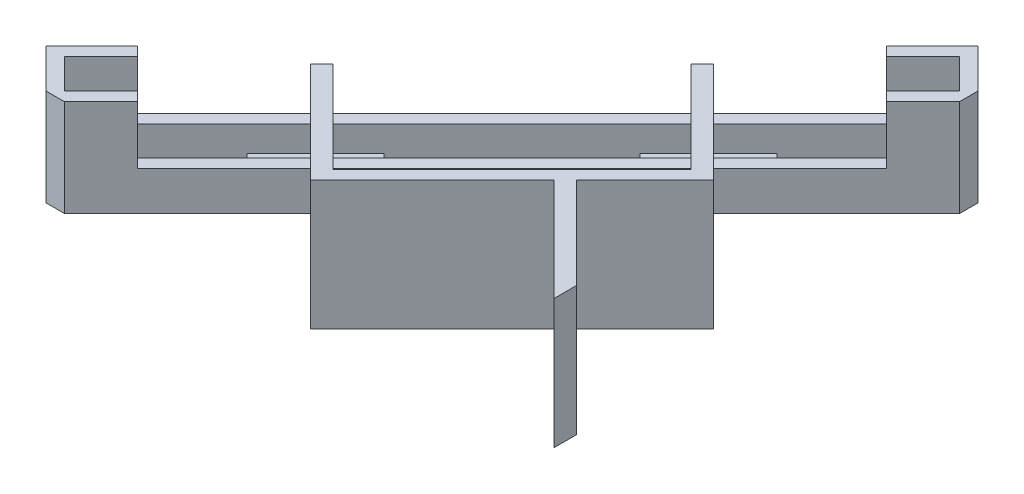
SolidWorks part; units mm, degrees
ref_plane "Front" through (0, 0, 0) normal (0, 0, 1) x (1, 0, 0)
ref_plane "Top" through (0, 0, 0) normal (0, 1, 0) x (1, 0, 0)
ref_plane "Right" through (0, 0, 0) normal (1, 0, 0) x (0, 0, -1)
sketch "Sketch1" plane through (0, 0, 0) normal (0, 1, 0) x (1, 0, 0)
  line L0 (-91.5986, 0) -> (0, 0)
  line L1 (0, 0) -> (0, 91.5986)
  line L2 (0, 91.5986) -> (-91.5986, 0)
  dimension "D1" = 129.54
extrude "Boss-Extrude1" add sketch "Sketch1" along normal blind 25.4
sketch "Sketch2" plane through (-45.7993, 0, -45.7993) normal (-0.7071, 0, -0.7071) x (-0.7071, 0, 0.7071)
  line L0 (-64.77, 19.05) -> (-62.23, 19.05)
  line L1 (-64.77, 25.4) -> (-64.77, 0) construction
  line L2 (-62.23, 19.05) -> (-62.23, 2.54)
  line L3 (-62.23, 2.54) -> (62.23, 2.54)
  line L4 (62.23, 2.54) -> (62.23, 19.05)
  line L5 (62.23, 19.05) -> (64.77, 19.05)
  line L6 (64.77, 25.4) -> (64.77, 0) construction
  line L7 (-64.77, 0) -> (64.77, 0) construction
  line L8 (-64.77, 25.4) -> (64.77, 25.4) construction
  line L9 (-64.77, 19.05) -> (-64.77, 0)
  line L10 (-64.77, 0) -> (64.77, 0)
  line L11 (64.77, 0) -> (64.77, 19.05)
  dimension "D1" = 2.54
  dimension "D2" = 2.54
  dimension "D3" = 2.54
  dimension "D4" = 6.35
  dimension "D5" = 6.35
extrude "Boss-Extrude2" add sketch "Sketch2" along normal blind 8.255
sketch "Sketch3" plane through (-51.6365, 0, -51.6365) normal (-0.7071, 0, -0.7071) x (-0.7071, 0, 0.7071)
  line L1 (-64.77, 0) -> (64.77, 0)
  line L2 (-64.77, 0) -> (-64.77, 19.05)
  line L3 (-64.77, 19.05) -> (64.77, 19.05)
  line L4 (64.77, 0) -> (64.77, 19.05)
extrude "Boss-Extrude3" add sketch "Sketch3" along normal blind 2.54
sketch "Sketch4" plane through (0, 25.4, 0) normal (0, 1, 0) x (1, 0, 0)
  line L0 (-50.8, 0) -> (0, 50.8)
  line L1 (-91.5986, 0) -> (0, 0) construction
  line L2 (0, 0) -> (0, 91.5986) construction
  line L3 (0, 50.8) -> (0, 0)
  line L4 (0, 0) -> (-50.8, 0)
  dimension "D1" = 50.8
  dimension "D2" = 50.8
sketch "Sketch5" plane through (45.7993, 0, -45.7993) normal (0.7071, 0, -0.7071) x (-0.7071, 0, -0.7071)
  line L0 (20.32, 12.7) -> (45.72, 12.7) construction
  line L1 (20.32, 12.7) -> (-5.08, 12.7) construction
  line L2 (45.72, 12.7) -> (64.77, 12.7) construction
  line L4 (20.32, 22.3266) -> (20.32, 12.7) construction
  line L5 (20.32, 12.7) -> (28.6569, 7.8867) construction
  line L6 (20.32, 12.7) -> (11.9831, 7.8867) construction
  line L7 (-5.08, 12.7) -> (0, 12.7) construction
  line L8 (0, 25.4) -> (0, 0) construction
  line L9 (64.77, 19.05) -> (64.77, 0) construction
  circle A0 centre (20.32, 12.7) radius 3.429
  circle A1 centre (45.72, 12.7) radius 3.556
  circle A2 centre (-5.08, 12.7) radius 3.556
  circle A3 centre (20.32, 22.3266) radius 2.032
  circle A4 centre (11.9831, 7.8867) radius 2.032
  circle A5 centre (28.6569, 7.8867) radius 2.032
  dimension "D1" = 6.858
  dimension "D2" = 7.112
  dimension "D4" = 7.112
  dimension "D5" = 4.064
  dimension "D3" = 25.4
  dimension "D6" = 9.6266
  dimension "D7" = 120
  dimension "D8" = 120
  dimension "D9" = 19.05
extrude "Cut-Extrude1" cut sketch "Sketch5" against normal through all
sketch "Sketch6" plane through (0, 25.4, 0) normal (0, 1, 0) x (1, 0, 0)
  line L0 (0, 8.2099) -> (-20.2056, 28.4154)
  line L6 (0, 0) -> (0, 91.5986) construction
  line L7 (-20.2056, 28.4154) -> (-48.621, 0)
  line L8 (-91.5986, 0) -> (0, 0) construction
  line L9 (0, 12.7) -> (-17.9605, 30.6605)
  line L10 (-17.9605, 30.6605) -> (0, 48.621)
  line L13 (0, 12.7) -> (-2.2451, 10.4549)
  line L15 (-44.1309, 4.4901) -> (-63.8236, 24.1829)
  line L17 (0, 91.5986) -> (-91.5986, 0) construction
  line L19 (-63.8236, 24.1829) -> (-88.0065, 0)
  line L20 (-88.0065, 0) -> (-91.5986, 0)
  line L21 (-91.5986, 0) -> (-89.8026, 1.7961)
  line L22 (-71.842, 19.7566) -> (-58.3717, 33.2269)
  line L23 (-33.2269, 58.3717) -> (-19.7566, 71.842)
  line L24 (-1.7961, 89.8026) -> (0, 91.5986)
  line L25 (0, 91.5986) -> (0, 88.0065)
  line L26 (0, 88.0065) -> (-24.1829, 63.8236)
  line L27 (-24.1829, 63.8236) -> (-4.4901, 44.1309)
  line L28 (-89.8026, 1.7961) -> (-71.842, 19.7566)
  line L29 (-89.8026, 1.7961) -> (-95.6397, 7.6332)
  line L30 (-71.842, 19.7566) -> (-77.6792, 25.5937)
  line L31 (-95.6397, 7.6332) -> (-77.6792, 25.5937)
  line L32 (-95.6397, 7.6332) -> (-7.6332, 95.6397) construction
  line L33 (-7.6332, 95.6397) -> (-1.7961, 89.8026)
  line L34 (-7.6332, 95.6397) -> (-25.5937, 77.6792)
  line L35 (-1.7961, 89.8026) -> (-19.7566, 71.842)
  line L36 (-25.5937, 77.6792) -> (-19.7566, 71.842)
  line L37 (-58.3717, 33.2269) -> (-33.2269, 58.3717)
  line L38 (-58.3717, 33.2269) -> (-64.2088, 39.0641)
  line L39 (-33.2269, 58.3717) -> (-39.0641, 64.2088)
  line L40 (-64.2088, 39.0641) -> (-39.0641, 64.2088)
  line L41 (-61.5786, 26.4279) -> (-26.4279, 61.5786)
  line L42 (-26.4279, 61.5786) -> (-8.5312, 43.6819)
  line L43 (-8.5312, 43.6819) -> (-43.6819, 8.5312)
  line L44 (-43.6819, 8.5312) -> (-61.5786, 26.4279)
  line L45 (-88.0065, 0) -> (-48.621, 0)
  line L46 (0, 0) -> (0, 8.2099)
  line L47 (0, 48.621) -> (0, 12.7)
  line L48 (0, 48.621) -> (0, 88.0065)
  line M1 (0, 91.5986) -> (-91.5986, 0)
  line M2 (-91.5986, 0) -> (0, 0)
  line M3 (0, 0) -> (0, 91.5986)
  dimension "D1" = 3.175
  dimension "D2" = 2.54
  dimension "D3" = 2.54
  dimension "D4" = 3.175
  dimension "D5" = 3.175
  dimension "D6" = 25.4
  dimension "D7" = 25.4
  dimension "D8" = 19.05
  dimension "D9" = 19.05
  dimension "D10" = 25.4
  dimension "D11" = 12.7
  dimension "D12" = 6.35
  dimension "D13" = 6.35
extrude "Cut-Extrude2" cut sketch "Sketch6" against normal through all contours L31 L29 L30 M1 | L15 L19 L7 M2 | L44 L43 L42 L41 | L40 L38 L39 M1 | L34 L36 L33 M1 | L10 L9 M3 | L0 L7 M2 M3 | L26 L27 L10 M3
sketch "Sketch7" plane through (-53.4325, 0, -53.4325) normal (-0.7071, 0, -0.7071) x (-0.7071, 0, 0.7071)
  line L0 (-64.77, 25.4) -> (-64.77, 19.05)
  line L1 (-64.77, 19.05) -> (-52.07, 19.05)
  line L2 (64.77, 19.05) -> (-64.77, 19.05) construction
  line L3 (-52.07, 19.05) -> (-52.07, 7.62)
  line L4 (-52.07, 7.62) -> (52.07, 7.62)
  line L5 (52.07, 7.62) -> (52.07, 19.05)
  line L6 (52.07, 19.05) -> (64.77, 19.05)
  line L7 (64.77, 19.05) -> (64.77, 25.4)
  line L8 (64.77, 25.4) -> (-64.77, 25.4)
  dimension "D1" = 12.7
  dimension "D2" = 12.7
  dimension "D3" = 11.43
extrude "Cut-Extrude3" cut sketch "Sketch7" against normal up to vertex (13.335 mm away) up to point (-88.0065, 25.4, 0)
sketch "Sketch8" plane through (-19.8204, 0, 19.8204) normal (-0.7071, 0, 0.7071) x (0.7071, 0, 0.7071)
  line L0 (-62.23, 25.4) -> (-62.23, 7.62)
  line L1 (-62.23, 7.62) -> (-64.77, 7.62)
  line L2 (-64.77, 7.62) -> (-62.23, 25.4)
  line L3 (-62.23, 7.62) -> (-62.23, 25.4) construction
extrude "Boss-Extrude4" add sketch "Sketch8" against normal up to vertex (3.175 mm away) up to point (-61.5786, 25.4, -26.4279)
sketch "Sketch9" plane through (17.5753, 0, -17.5753) normal (-0.7071, 0, 0.7071) x (0.7071, 0, 0.7071)
  line L0 (-62.23, 25.4) -> (-62.23, 7.62)
  line L1 (-62.23, 7.62) -> (-64.77, 7.62)
  line L2 (-64.77, 7.62) -> (-62.23, 25.4)
  line L3 (-62.23, 25.4) -> (-62.23, 7.62) construction
extrude "Boss-Extrude5" add sketch "Sketch9" against normal up to vertex (3.175 mm away) up to point (-24.1829, 25.4, -63.8236)
